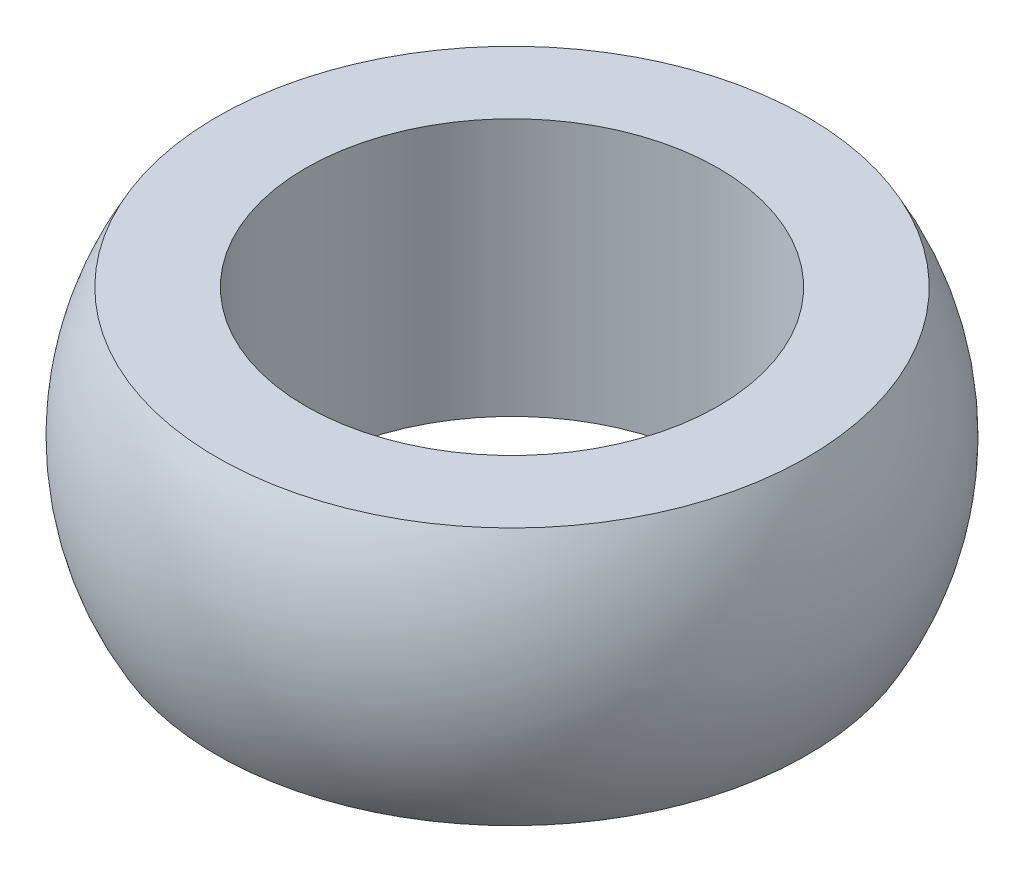
SolidWorks part; units mm, degrees
material "Cast Carbon Steel"
ref_plane "Front Plane" through (0, 0, 0) normal (0, 0, 1) x (1, 0, 0)
ref_plane "Top Plane" through (0, 0, 0) normal (0, 1, 0) x (1, 0, 0)
ref_plane "Right Plane" through (0, 0, 0) normal (1, 0, 0) x (0, 0, -1)
sketch "Sketch1" plane through (0, 0, 0) normal (0, 0, 1) x (1, 0, 0)
  line L0 (0, 0) -> (20, 0) construction
  line L1 (0, 0) -> (0, 10.8664) construction
  line L2 (12, -7.5) -> (17.1665, -7.5)
  line L3 (12, 7.5) -> (17.1665, 7.5)
  line L4 (12, 7.5) -> (12, -7.5)
  line L5 (0, 7.5) -> (20, 7.5) construction
  line L6 (0, -7.5) -> (20, -7.5) construction
  arc A0 (17.1665, -7.5) -> (17.1665, 7.5) centre (4.1761, 0) ccw
  dimension "D1" = 30
  dimension "D2" = 20
  dimension "D5" = 12
  dimension "D3" = 7.5
  dimension "D4" = 7.5
revolve "Revolve1" add sketch "Sketch1" angle 360 about L1
